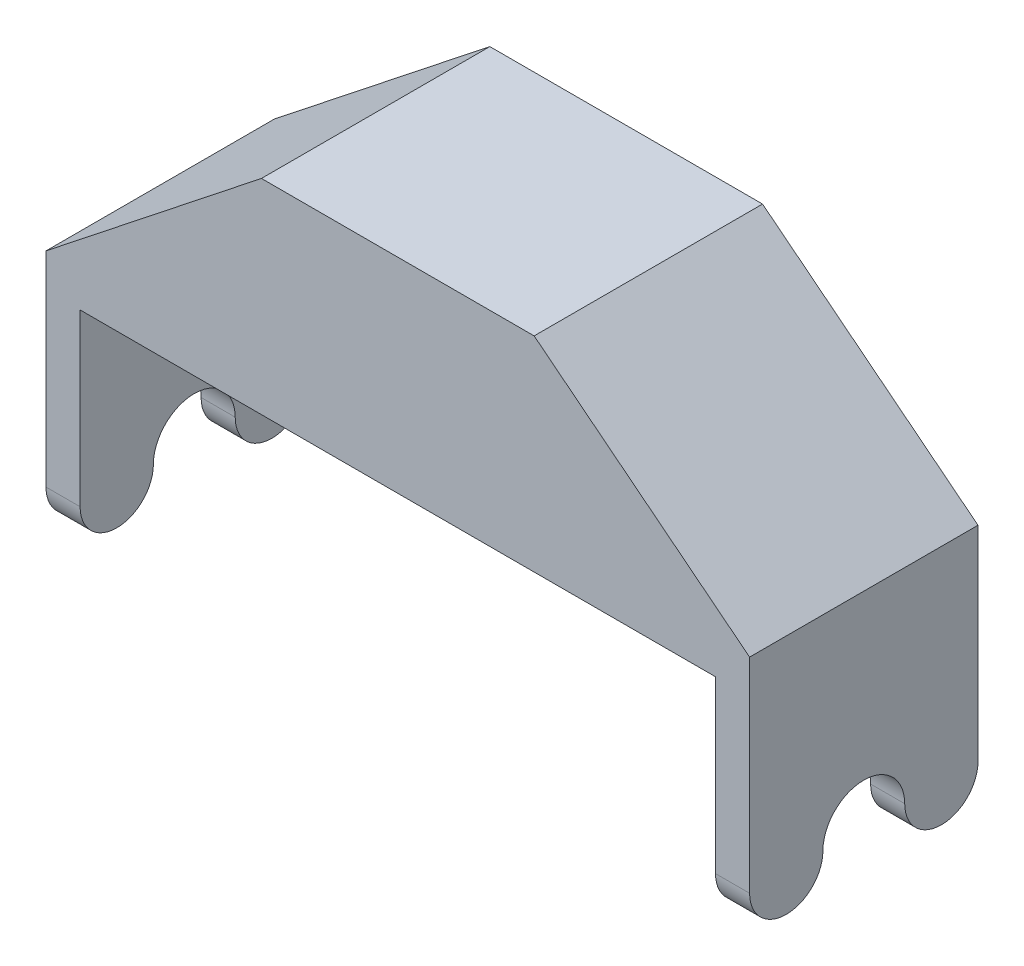
SolidWorks part; units mm, degrees
ref_plane "前视基准面" through (0, 0, 0) normal (0, 0, 1) x (1, 0, 0)
ref_plane "上视基准面" through (0, 0, 0) normal (0, 1, 0) x (1, 0, 0)
ref_plane "右视基准面" through (0, 0, 0) normal (1, 0, 0) x (0, 0, -1)
sketch "草图1" plane through (0, 0, 0) normal (0, 0, 1) x (1, 0, 0)
  line L0 (-2.4052, -0.0763) -> (-130.7806, -0.0763) construction
  line L1 (0, 0) -> (0, 37.5806) construction
  line L7 (51.6, -0.0763) -> (51.6, 29.9237)
  line L8 (51.6, 29.9237) -> (20, 54.9237)
  line L9 (20, 54.9237) -> (-20, 54.9237)
  line L10 (-20, 54.9237) -> (-51.6, 29.9237)
  line L11 (-51.6, 29.9237) -> (-51.6, -0.0763)
  line L12 (-51.6, -0.0763) -> (51.6, -0.0763)
  dimension "D1" = 103.2
  dimension "D2" = 55
  dimension "D5" = 30
  dimension "D6" = 40
extrude "凸台-拉伸1" add sketch "草图1" along normal blind 33.5
sketch "草图6" plane through (-51.6, 0, 0) normal (-1, 0, 0) x (0, 0, 1)
  line L0 (33.5, -0.0763) -> (0, -0.0763) construction
  circle A0 centre (16.75, -0.0763) radius 6
  dimension "D1" = 12
extrude "切除-拉伸2" cut sketch "草图6" against normal up to surface (103.2 mm away) up to face at (51.6, 14.9237, 16.75)
sketch "草图7" plane through (-51.6, 0, 0) normal (-1, 0, 0) x (0, 0, 1)
  line L0 (10.75, -0.0763) -> (0, -0.0763) construction
  line L1 (33.5, -0.0763) -> (22.75, -0.0763) construction
  circle A0 centre (5.375, -0.0763) radius 5.375
  circle A1 centre (28.125, -0.0763) radius 5.375
extrude "凸台-拉伸3" add sketch "草图7" against normal up to surface (103.2 mm away) up to face at (51.6, 10.9237, 16.75)
sketch "草图8" plane through (0, 0, 33.5) normal (0, 0, 1) x (1, 0, 0)
  line L0 (0, -0.0763) -> (0, 61.1377) construction
  line L2 (-46.6, -0.0763) -> (-46.6, 24.9237)
  line L3 (-51.6, -0.0763) -> (51.6, -0.0763) construction
  line L4 (-46.6, 24.9237) -> (46.6, 24.9237)
  line L5 (46.6, 24.9237) -> (46.6, -0.0763)
  line L7 (-46.6, -0.0763) -> (-46.6, -12.1113)
  line L8 (-46.6, -12.1113) -> (46.6, -12.1113)
  line L9 (46.6, -12.1113) -> (46.6, -0.0763)
  dimension "D1" = 93.2
  dimension "D2" = 25
extrude "切除-拉伸3" cut sketch "草图8" against normal up to surface (33.5 mm away) up to face at (0, 28.2571, 0)
